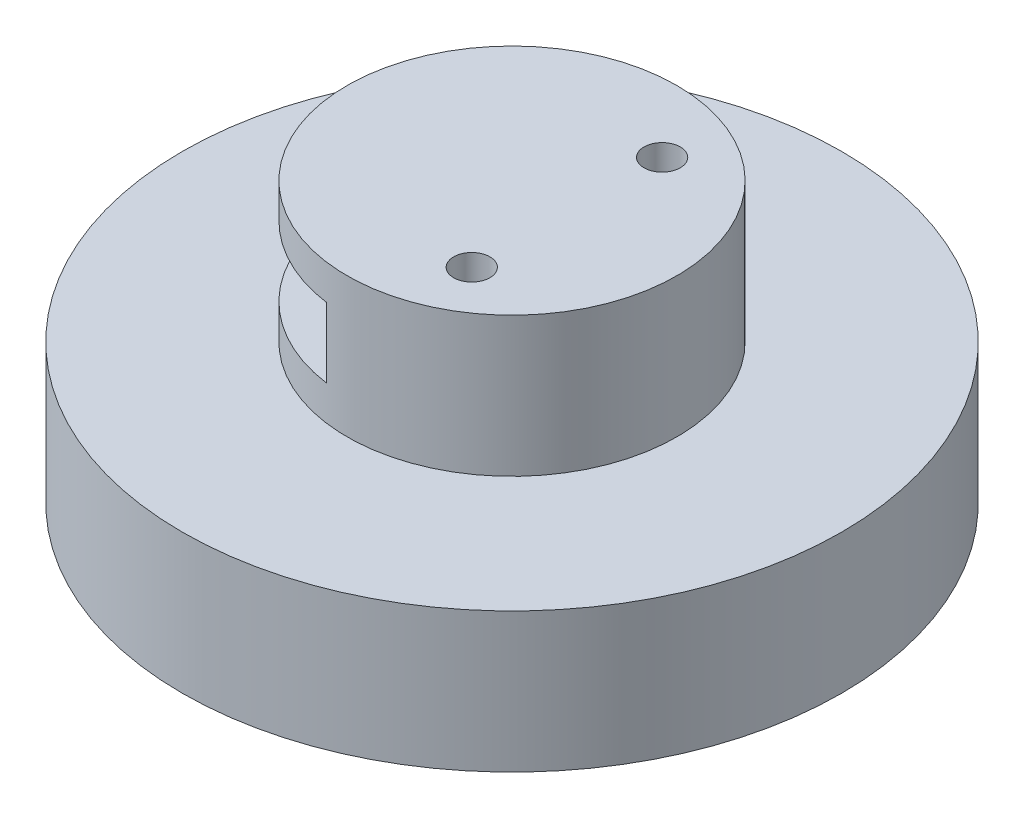
SolidWorks part; units mm, degrees
material "AISI 304"
ref_plane "Front Plane" through (0, 0, 0) normal (0, 0, 1) x (1, 0, 0)
ref_plane "Top Plane" through (0, 0, 0) normal (0, 1, 0) x (1, 0, 0)
ref_plane "Right Plane" through (0, 0, 0) normal (1, 0, 0) x (0, 0, -1)
sketch "Sketch1" plane through (0, 0, 0) normal (0, 0, 1) x (1, 0, 0)
  line L0 (0, 12.7) -> (-15, 12.7)
  line L1 (-15, 12.7) -> (-15, 0)
  line L2 (-15, 0) -> (-30, 0)
  line L3 (-30, 0) -> (-30, -12.7)
  line L4 (-30, -12.7) -> (0, -12.7)
  line L5 (0, -12.7) -> (0, 12.7)
  dimension "D1" = 12.7
  dimension "D2" = 30
  dimension "D3" = 15
revolve "Revolve1" add sketch "Sketch1" angle 360 about L5
sketch "Sketch2" plane through (0, 0, 0) normal (0, 0, 1) x (1, 0, 0)
  line L0 (-15, 12.7) -> (-15, 0) construction
  line L1 (-15, 9.525) -> (-2, 9.525)
  line L2 (-15, 9.525) -> (-15, 3.175)
  line L3 (-15, 3.175) -> (-2, 3.175)
  line L4 (-2, 9.525) -> (-2, 3.175)
  line L5 (15, 12.7) -> (-15, 12.7) construction
  line L6 (15, 0) -> (-15, 0) construction
  dimension "D1" = 3.175
  dimension "D2" = 3.175
  dimension "D3" = 2
extrude "Cut-Extrude1" cut sketch "Sketch2" against normal through all both and the other way through all
hole_wizard "M4x0.7 Tapped Hole1" positions "Sketch3" profile "Sketch4" tap size "M4x0.7" standard "ANSI Metric"
sketch "Sketch3" plane through (0, 12.7, 0) normal (0, 1, 0) x (1, 0, 0)
  line L0 (-10, 0) -> (0, 0) construction
  line L1 (0, 0) -> (5, 8.6603) construction
  line L3 (5, -8.6603) -> (0, 0) construction
  point P5 (5, 8.6603)
  point P7 (5, -8.6603)
  dimension "D1" = 120
  dimension "D2" = 120
  dimension "D3" = 10
sketch "Sketch4" plane through (5, 12.7, 8.6603) normal (1, 0, 0) x (0, 0, 1)
  line L0 (0, 0) -> (0, 11.0914)
  line L1 (0, 11.0914) -> (1.65, 10.1)
  line L2 (1.65, 10.1) -> (1.65, 0)
  line L5 (1.65, 0) -> (0, 0)
  line L10 (0, 11.0914) -> (-1.65, 10.1) construction
  line L11 (0, -6.35) -> (0, 107.95) construction
  dimension "Tap Drill Dia." = 3.3
  dimension "Tap Drill Depth" = 10.1
  dimension "Drill Angle" = 118
cosmetic thread "Hole Thread1" parameters "D1"=8, "D2"=4
cosmetic thread "Hole Thread2" parameters "D1"=8, "D2"=4
hole_wizard "M4x0.7 Tapped Hole2" positions "Sketch5" profile "Sketch6" tap size "M4x0.7" standard "ANSI Metric"
sketch "Sketch5" plane through (0, -12.7, 0) normal (0, -1, 0) x (-1, 0, 0)
  line L0 (-20, 0) -> (0, 0) construction
  line L1 (0, 0) -> (10, -17.3205) construction
  line L3 (0, 0) -> (10, 17.3205) construction
  point P1 (-20, 0)
  point P5 (10, -17.3205)
  point P10 (10, 17.3205)
  dimension "D1" = 120
  dimension "D2" = 120
  dimension "D3" = 20
sketch "Sketch6" plane through (20, -12.7, 0) normal (1, 0, 0) x (0, 0, -1)
  line L0 (0, 0) -> (0, 11.0914)
  line L1 (0, 11.0914) -> (1.65, 10.1)
  line L2 (1.65, 10.1) -> (1.65, 0)
  line L5 (1.65, 0) -> (0, 0)
  line L10 (0, 11.0914) -> (-1.65, 10.1) construction
  line L11 (0, -6.35) -> (0, 107.95) construction
  dimension "Tap Drill Dia." = 3.3
  dimension "Tap Drill Depth" = 10.1
  dimension "Drill Angle" = 118
cosmetic thread "Hole Thread3" parameters "D1"=8, "D2"=4
cosmetic thread "Hole Thread4" parameters "D1"=8, "D2"=4
cosmetic thread "Hole Thread5" parameters "D1"=8, "D2"=4
